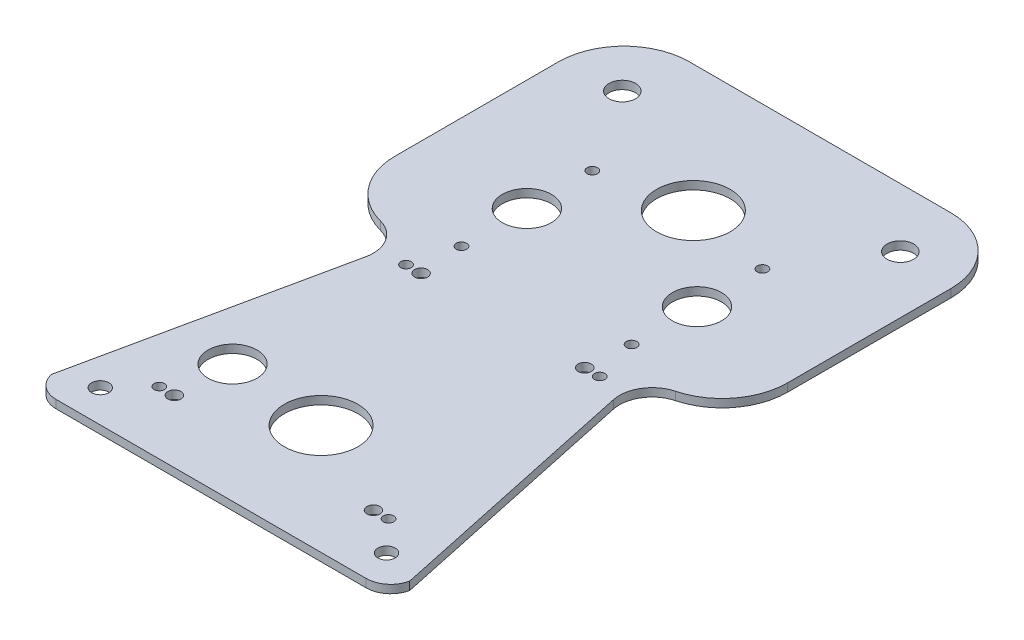
SolidWorks part; units mm, degrees
material "6061-T6 (SS)"
ref_plane "Front Plane" through (0, 0, 0) normal (0, 0, 1) x (1, 0, 0)
ref_plane "Top Plane" through (0, 0, 0) normal (0, 1, 0) x (1, 0, 0)
ref_plane "Right Plane" through (0, 0, 0) normal (1, 0, 0) x (0, 0, -1)
ref_plane "Plane1" through (0, 3.175, 0) normal (0, 1, 0) x (1, 0, 0)
sketch "Sketch1" plane through (0, 3.175, 0) normal (0, 1, 0) x (1, 0, 0)
  line L0 (457.2, 73.787) -> (457.2, -3.937)
  line L1 (457.2, -3.937) -> (812.8, -3.937)
  line L2 (812.8, -3.937) -> (812.8, 73.787)
  line L3 (812.8, 73.787) -> (457.2, 73.787)
  dimension "D1" = 355.6
extrude "Boss-Extrude1" add sketch "Sketch1" against normal blind 22.225
sketch "Sketch2" plane through (812.8, 0, 0) normal (1, 0, 0) x (0, 0, -1)
  line L0 (70.612, -19.05) -> (70.612, 0)
  line L1 (70.612, 0) -> (-3.937, 0)
  line L2 (-3.937, 0) -> (-3.937, -19.05)
  line L3 (-3.937, -19.05) -> (70.612, -19.05)
extrude "Cut-Extrude1" cut sketch "Sketch2" against normal through all
sketch "Sketch3" plane through (0, 3.175, 0) normal (0, 1, 0) x (-1, 0, 0)
  line L0 (-482.6, 3.937) -> (-482.6, 0)
  line L1 (-482.6, 0) -> (-457.2, 0)
  line L2 (-457.2, 0) -> (-457.2, 3.937)
  line L3 (-457.2, 3.937) -> (-482.6, 3.937)
extrude "Cut-Extrude2" cut sketch "Sketch3" against normal through all
sketch "Sketch4" plane through (0, 3.175, 0) normal (0, 1, 0) x (-1, 0, 0)
  line L0 (-812.8, 3.937) -> (-482.6, 3.937)
  line L1 (-482.6, 3.937) -> (-482.6, 0.762)
  line L2 (-482.6, 0.762) -> (-812.8, 0.762)
  line L3 (-812.8, 0.762) -> (-812.8, 3.937)
extrude "Boss-Extrude2" add sketch "Sketch4" along normal blind 15.875
sketch "Sketch5" plane through (457.2, 0, 0) normal (-1, 0, 0) x (0, 0, 1)
  line L0 (0, 3.175) -> (0, 0)
  line L1 (0, 0) -> (-69.85, 0)
  line L2 (-69.85, 0) -> (-69.85, 3.175)
  line L3 (-69.85, 3.175) -> (0, 3.175)
extrude "Boss-Extrude3" add sketch "Sketch5" along normal blind 457.2
sketch "Sketch6" plane through (0, 0, 0) normal (0, 0, 1) x (1, 0, 0)
  line L0 (330.2, 3.175) -> (330.2, 0)
  line L1 (330.2, 0) -> (0, 0)
  line L2 (0, 0) -> (0, 3.175)
  line L3 (0, 3.175) -> (330.2, 3.175)
extrude "Boss-Extrude4" add sketch "Sketch6" along normal blind 3.937
sketch "Sketch7" plane through (0, 3.175, 0) normal (0, 1, 0) x (-1, 0, 0)
  line L0 (-330.2, 3.937) -> (0, 3.937)
  line L1 (0, 3.937) -> (0, 0.762)
  line L2 (0, 0.762) -> (-330.2, 0.762)
  line L3 (-330.2, 0.762) -> (-330.2, 3.937)
extrude "Boss-Extrude5" add sketch "Sketch7" along normal blind 15.875
sketch "Sketch8" plane through (0, 0, -69.85) normal (0, 0, -1) x (-1, 0, 0)
  line L0 (-355.6, 0) -> (-355.6, 3.175)
  line L1 (-355.6, 3.175) -> (0, 3.175)
  line L2 (0, 3.175) -> (0, 0)
  line L3 (0, 0) -> (-355.6, 0)
extrude "Boss-Extrude6" add sketch "Sketch8" along normal blind 3.937
sketch "Sketch9" plane through (0, 0, 0) normal (0, -1, 0) x (1, 0, 0)
  line L0 (0, -70.612) -> (355.6, -70.612)
  line L1 (355.6, -70.612) -> (355.6, -73.787)
  line L2 (355.6, -73.787) -> (0, -73.787)
  line L3 (0, -73.787) -> (0, -70.612)
extrude "Boss-Extrude7" add sketch "Sketch9" along normal blind 19.05
sketch "Sketch10" plane through (0, 0, -69.85) normal (0, 0, -1) x (-1, 0, 0)
  line L0 (-444.5794, 3.175) -> (-368.2206, 3.175)
  line L1 (-368.2206, 3.175) -> (-368.2206, 0)
  line L2 (-368.2206, 0) -> (-444.5794, 0)
  line L3 (-444.5794, 0) -> (-444.5794, 3.175)
extrude "Boss-Extrude8" add sketch "Sketch10" along normal blind 27.432
sketch "Sketch11" plane through (0, 0, 0) normal (0, 0, 1) x (1, 0, 0)
  line L0 (344.3735, 3.175) -> (468.4265, 3.175)
  line L1 (468.4265, 3.175) -> (468.4265, 0)
  line L2 (468.4265, 0) -> (344.3735, 0)
  line L3 (344.3735, 0) -> (344.3735, 3.175)
extrude "Boss-Extrude9" add sketch "Sketch11" along normal blind 19.05
draft "Draft1" type of draft neutral plane draft angle 30 faces to draft 2 face at (344.3735, 1.5875, 9.525) face at (468.4265, 1.5875, 9.525) neutral plane through (0, 0, 19.05) neutral plane normal (0, 0, 1) parameters "D1"=30
draft "Draft2" type of draft neutral plane draft angle 19 faces to draft 2 face at (368.2206, 1.5875, -83.566) face at (444.5794, 1.5875, -83.566) neutral plane through (0, 0, -97.282) neutral plane normal (0, 0, -1) parameters "D1"=19
hole_wizard "M20 Clearance Hole1" positions "Sketch13" profile "Sketch12" hole size "M20" standard "ANSI Metric"
sketch "Sketch13" plane through (0, 0, 0) normal (0, -1, 0) x (-1, 0, 0)
  point P0 (-624.2546, 36.83)
sketch "Sketch12" plane through (624.2546, 0, -36.83) normal (1, 0, 0) x (0, 0, -1)
  line L0 (0, 0) -> (0, 19.05)
  line L1 (0, 19.05) -> (11.1125, 19.05)
  line L2 (11.1125, 19.05) -> (11.1125, 0)
  line L5 (11.1125, 0) -> (0, 0)
  line L11 (0, -6.35) -> (0, 107.95) construction
  dimension "Thru Hole Dia." = 22.225
  dimension "Thru Hole Depth" = 19.05
hole_wizard "Hole1" positions "Sketch15" profile "Sketch14" legacy
sketch "Sketch15" plane through (0, 3.175, 0) normal (0, 1, 0) x (1, 0, 0)
  point P0 (229.2616, 36.83)
  point P1 (229.2616, 62.23)
  point P2 (229.2616, 11.43)
sketch "Sketch14" plane through (229.2616, 3.175, -36.83) normal (1, 0, 0) x (0, 0, 1)
  line L0 (0, 0) -> (0, 22.225)
  line L1 (0, 22.225) -> (4.064, 22.225)
  line L2 (4.064, 22.225) -> (4.064, 0)
  line L3 (4.064, 0) -> (0, 0)
  line L4 (0, 110) -> (0, -10) construction
  dimension "Diameter" = 8.128
  dimension "Depth" = 22.225
hole_wizard "M25 Clearance Hole1" positions "Sketch17" profile "Sketch16" hole size "M25" standard "ANSI Metric"
sketch "Sketch17" plane through (0, 3.175, 0) normal (0, 1, 0) x (1, 0, 0)
  point P0 (147.8292, 36.83)
sketch "Sketch16" plane through (147.8292, 3.175, -36.83) normal (1, 0, 0) x (0, 0, 1)
  line L0 (0, 0) -> (0, 22.225)
  line L1 (0, 22.225) -> (14.2875, 22.225)
  line L2 (14.2875, 22.225) -> (14.2875, 0)
  line L5 (14.2875, 0) -> (0, 0)
  line L11 (0, -6.35) -> (0, 107.95) construction
  dimension "Thru Hole Dia." = 28.575
  dimension "Thru Hole Depth" = 22.225
hole_wizard "M3 Clearance Hole1" positions "Sketch19" profile "Sketch18" hole size "M3" standard "ANSI Metric"
sketch "Sketch19" plane through (0, 3.175, 0) normal (0, 1, 0) x (1, 0, 0)
  point P0 (120.6004, 65.405)
  point P1 (120.6004, 8.255)
  point P2 (237.4404, 8.255)
  point P3 (237.4404, 65.405)
sketch "Sketch18" plane through (120.6004, 3.175, -65.405) normal (1, 0, 0) x (0, 0, 1)
  line L0 (0, 0) -> (0, 22.225)
  line L1 (0, 22.225) -> (1.7859, 22.225)
  line L2 (1.7859, 22.225) -> (1.7859, 0)
  line L5 (1.7859, 0) -> (0, 0)
  line L11 (0, -6.35) -> (0, 107.95) construction
  dimension "Thru Hole Dia." = 3.5719
  dimension "Thru Hole Depth" = 22.225
hole_wizard "M2 Clearance Hole1" positions "Sketch21" profile "Sketch20" hole size "M2" standard "ANSI Metric"
sketch "Sketch21" plane through (0, 3.175, 0) normal (0, 1, 0) x (1, 0, 0)
  point P0 (101.6, 3.175)
  point P1 (101.6, 66.675)
  point P2 (50.8, 66.675)
  point P3 (50.8, 3.175)
  point P4 (762, 66.675)
  point P5 (762, 3.175)
  point P6 (711.2, 3.175)
  point P7 (711.2, 66.675)
sketch "Sketch20" plane through (101.6, 3.175, -3.175) normal (1, 0, 0) x (0, 0, 1)
  line L0 (0, 0) -> (0, 22.225)
  line L1 (0, 22.225) -> (1.27, 22.225)
  line L2 (1.27, 22.225) -> (1.27, 0)
  line L5 (1.27, 0) -> (0, 0)
  line L11 (0, -6.35) -> (0, 107.95) construction
  dimension "Thru Hole Dia." = 2.54
  dimension "Thru Hole Depth" = 22.225
hole_wizard "M3.5 Clearance Hole1" positions "Sketch23" profile "Sketch22" hole size "M3.5" standard "ANSI Metric"
sketch "Sketch23" plane through (0, 3.175, 0) normal (0, 1, 0) x (1, 0, 0)
  point P0 (443.992, 87.8535)
  point P1 (368.808, 87.8535)
  point P2 (361.9119, -1.0389)
  point P3 (450.8881, -1.0389)
sketch "Sketch22" plane through (443.992, 3.175, -87.8535) normal (1, 0, 0) x (0, 0, 1)
  line L0 (0, 0) -> (0, 22.225)
  line L1 (0, 22.225) -> (2.032, 22.225)
  line L2 (2.032, 22.225) -> (2.032, 0)
  line L5 (2.032, 0) -> (0, 0)
  line L11 (0, -6.35) -> (0, 107.95) construction
  dimension "Thru Hole Dia." = 4.064
  dimension "Thru Hole Depth" = 22.225
hole_wizard "Hole2" positions "Sketch25" profile "Sketch24" legacy
sketch "Sketch25" plane through (0, 3.175, 0) normal (0, 1, 0) x (1, 0, 0)
  point P0 (438.15, 87.8535)
  point P1 (374.65, 87.8535)
  point P2 (445.0461, -1.0389)
  point P3 (367.7539, -1.0389)
  point P4 (115.5204, 65.405)
  point P5 (115.5204, 8.255)
  point P6 (242.5204, 8.255)
  point P7 (242.5204, 65.405)
sketch "Sketch24" plane through (438.15, 3.175, -87.8535) normal (1, 0, 0) x (0, 0, 1)
  line L0 (0, 0) -> (0, 22.225)
  line L1 (0, 22.225) -> (2.54, 22.225)
  line L2 (2.54, 22.225) -> (2.54, 0)
  line L3 (2.54, 0) -> (0, 0)
  line L4 (0, 110) -> (0, -10) construction
  dimension "Diameter" = 5.08
  dimension "Depth" = 22.225
hole_wizard "M20 Clearance Hole2" [suppressed] positions "Sketch27" profile "Sketch26" hole size "M20" standard "ANSI Metric"
sketch "Sketch27" plane through (0, 3.175, 0) normal (0, 1, 0) x (1, 0, 0)
  point P0 (406.4, 57.9628)
  point P1 (188.5454, 36.83)
sketch "Sketch26" plane through (406.4, 3.175, -57.9628) normal (1, 0, 0) x (0, 0, 1)
  line L0 (0, 0) -> (0, 22.225)
  line L1 (0, 22.225) -> (11.1125, 22.225)
  line L2 (11.1125, 22.225) -> (11.1125, 0)
  line L5 (11.1125, 0) -> (0, 0)
  line L11 (0, -6.35) -> (0, 107.95) construction
  dimension "Thru Hole Dia." = 22.225
  dimension "Thru Hole Depth" = 22.225
hole_wizard "M25 Clearance Hole2" positions "Sketch31" profile "Sketch30" hole size "M25" standard "ANSI Metric"
sketch "Sketch31" plane through (0, 0, 0) normal (0, -1, 0) x (-1, 0, 0)
  point P0 (-406.4, 17.272)
  point P1 (-664.9708, 36.83)
sketch "Sketch30" plane through (406.4, 0, -17.272) normal (1, 0, 0) x (0, 0, -1)
  line L0 (0, 0) -> (0, 19.05)
  line L1 (0, 19.05) -> (14.2875, 19.05)
  line L2 (14.2875, 19.05) -> (14.2875, 0)
  line L5 (14.2875, 0) -> (0, 0)
  line L11 (0, -6.35) -> (0, 107.95) construction
  dimension "Thru Hole Dia." = 28.575
  dimension "Thru Hole Depth" = 19.05
hole_wizard "Hole3" positions "Sketch33" profile "Sketch32" legacy
sketch "Sketch33" plane through (0, 0, 0) normal (0, -1, 0) x (-1, 0, 0)
  point P0 (-570.2796, 8.255)
  point P1 (-570.2796, 65.405)
  point P2 (-697.2796, 65.405)
  point P3 (-697.2796, 8.255)
sketch "Sketch32" plane through (570.2796, 0, -8.255) normal (1, 0, 0) x (0, 0, -1)
  line L0 (0, 0) -> (0, 19.05)
  line L1 (0, 19.05) -> (2.5527, 19.05)
  line L2 (2.5527, 19.05) -> (2.5527, 0)
  line L3 (2.5527, 0) -> (0, 0)
  line L4 (0, 110) -> (0, -10) construction
  dimension "Diameter" = 5.1054
  dimension "Depth" = 19.05
hole_wizard "Hole4" positions "Sketch35" profile "Sketch34" legacy
sketch "Sketch35" plane through (0, 0, 0) normal (0, -1, 0) x (-1, 0, 0)
  point P0 (-583.5384, 11.43)
  point P1 (-583.5384, 36.83)
  point P2 (-583.5384, 62.23)
sketch "Sketch34" plane through (583.5384, 0, -11.43) normal (1, 0, 0) x (0, 0, -1)
  line L0 (0, 0) -> (0, 19.05)
  line L1 (0, 19.05) -> (4.064, 19.05)
  line L2 (4.064, 19.05) -> (4.064, 0)
  line L3 (4.064, 0) -> (0, 0)
  line L4 (0, 110) -> (0, -10) construction
  dimension "Diameter" = 8.128
  dimension "Depth" = 19.05
hole_wizard "M3 Clearance Hole2" positions "Sketch37" profile "Sketch36" hole size "M3" standard "ANSI Metric"
sketch "Sketch37" plane through (0, 0, 0) normal (0, -1, 0) x (-1, 0, 0)
  point P0 (-692.1996, 8.255)
  point P1 (-692.1996, 65.405)
  point P2 (-575.3596, 65.405)
  point P3 (-575.3596, 8.255)
sketch "Sketch36" plane through (692.1996, 0, -8.255) normal (1, 0, 0) x (0, 0, -1)
  line L0 (0, 0) -> (0, 19.05)
  line L1 (0, 19.05) -> (1.7859, 19.05)
  line L2 (1.7859, 19.05) -> (1.7859, 0)
  line L5 (1.7859, 0) -> (0, 0)
  line L11 (0, -6.35) -> (0, 107.95) construction
  dimension "Thru Hole Dia." = 3.5719
  dimension "Thru Hole Depth" = 19.05
hole_wizard "M6 Clearance Hole1" positions "Sketch39" profile "Sketch38" hole size "M6" standard "ANSI Metric"
sketch "Sketch39" plane through (0, 3.175, 0) normal (0, 1, 0) x (1, 0, 0)
  point P0 (612.775, 10.287)
  point P1 (498.475, 10.287)
  point P2 (314.325, 10.287)
  point P3 (200.025, 10.287)
  point P4 (628.3192, 61.976)
  point P5 (184.4808, 61.976)
  point P6 (690.88, 15.875)
  point P7 (739.902, 9.525)
  point P8 (121.92, 15.875)
  point P9 (72.898, 9.525)
  point P10 (298.8745, 17.5473)
  point P11 (513.9255, 17.5473)
  point P12 (165.1, 14.732)
  point P13 (266.7, 14.732)
  point P14 (546.1, 14.732)
  point P15 (647.7, 14.732)
  point P16 (330.2, 61.722)
  point P17 (279.4, 61.722)
  point P18 (139.7, 61.722)
  point P19 (25.4, 61.722)
  point P20 (482.6, 61.722)
  point P21 (533.4, 61.722)
  point P22 (673.1, 61.722)
  point P23 (787.4, 61.722)
  point P24 (6.35, 39.497)
  point P25 (806.45, 39.497)
  point P26 (350.8375, -12.8905)
  point P27 (461.9625, -12.8905)
sketch "Sketch38" plane through (612.775, 3.175, -10.287) normal (1, 0, 0) x (0, 0, 1)
  line L0 (0, 0) -> (0, 22.225)
  line L1 (0, 22.225) -> (3.3528, 22.225)
  line L2 (3.3528, 22.225) -> (3.3528, 0)
  line L5 (3.3528, 0) -> (0, 0)
  line L11 (0, -6.35) -> (0, 107.95) construction
  dimension "Thru Hole Dia." = 6.7056
  dimension "Thru Hole Depth" = 22.225
hole_wizard "M6 Clearance Hole2" positions "Sketch41" profile "Sketch40" hole size "M6" standard "ANSI Metric"
sketch "Sketch41" plane through (0, 0, 3.937) normal (0, 0, 1) x (1, 0, 0)
  point P0 (495.3, 12.7)
  point P1 (520.7, 12.7)
  point P2 (546.1, 12.7)
  point P3 (571.5, 12.7)
  point P4 (596.9, 12.7)
  point P5 (622.3, 12.7)
  point P6 (647.7, 12.7)
  point P7 (673.1, 12.7)
  point P8 (698.5, 12.7)
  point P9 (723.9, 12.7)
  point P10 (749.3, 12.7)
  point P11 (774.7, 12.7)
  point P12 (800.1, 12.7)
  point P13 (317.5, 12.7)
  point P14 (292.1, 12.7)
  point P15 (266.7, 12.7)
  point P16 (241.3, 12.7)
  point P17 (215.9, 12.7)
  point P18 (190.5, 12.7)
  point P19 (165.1, 12.7)
  point P20 (139.7, 12.7)
  point P21 (114.3, 12.7)
  point P22 (88.9, 12.7)
  point P23 (63.5, 12.7)
  point P24 (12.7, 12.7)
  point P25 (38.1, 12.7)
sketch "Sketch40" plane through (495.3, 12.7, 3.937) normal (1, 0, 0) x (0, -1, 0)
  line L0 (0, 0) -> (0, 101.219)
  line L1 (0, 101.219) -> (3.3528, 101.219)
  line L2 (3.3528, 101.219) -> (3.3528, 0)
  line L5 (3.3528, 0) -> (0, 0)
  line L11 (0, -6.35) -> (0, 107.95) construction
  dimension "Thru Hole Dia." = 6.7056
  dimension "Thru Hole Depth" = 101.219
hole_wizard "M5 Clearance Hole1" positions "Sketch43" profile "Sketch42" hole size "M5" standard "ANSI Metric"
sketch "Sketch43" plane through (0, 0, -73.787) normal (0, 0, -1) x (-1, 0, 0)
  point P0 (-469.9, -12.7)
  point P1 (-495.3, -12.7)
  point P2 (-520.7, -12.7)
  point P3 (-546.1, -12.7)
  point P4 (-571.5, -12.7)
  point P5 (-596.9, -12.7)
  point P6 (-622.3, -12.7)
  point P7 (-647.7, -12.7)
  point P8 (-673.1, -12.7)
  point P9 (-698.5, -12.7)
  point P10 (-723.9, -12.7)
  point P11 (-749.3, -12.7)
  point P12 (-774.7, -12.7)
  point P13 (-800.1, -12.7)
  point P14 (-342.9, -12.7)
  point P15 (-317.5, -12.7)
  point P16 (-292.1, -12.7)
  point P17 (-266.7, -12.7)
  point P18 (-241.3, -12.7)
  point P19 (-215.9, -12.7)
  point P20 (-190.5, -12.7)
  point P21 (-165.1, -12.7)
  point P22 (-139.7, -12.7)
  point P23 (-114.3, -12.7)
  point P24 (-88.9, -12.7)
  point P25 (-63.5, -12.7)
  point P26 (-38.1, -12.7)
  point P27 (-12.7, -12.7)
sketch "Sketch42" plane through (469.9, -12.7, -73.787) normal (1, 0, 0) x (0, 1, 0)
  line L0 (0, 0) -> (0, 92.837)
  line L1 (0, 92.837) -> (2.667, 92.837)
  line L2 (2.667, 92.837) -> (2.667, 0)
  line L5 (2.667, 0) -> (0, 0)
  line L11 (0, -6.35) -> (0, 107.95) construction
  dimension "Thru Hole Dia." = 5.334
  dimension "Thru Hole Depth" = 92.837
chamfer "Chamfer1" distance 3.175 angle 45 8 edges at (482.6, 19.05, 2.3495) (0, 19.05, 2.3495) (812.8, 19.05, 2.3495) (812.8, -19.05, -72.1995) (457.2, -19.05, -72.1995) (0, -19.05, -72.1995) (330.2, 19.05, 2.3495) (355.6, -19.05, -72.1995)
fillet "Fillet1" radius 0.762 4 edges at (177.8, 0, -70.612) (635, 0, -70.612) (165.1, 3.175, 0.762)
fillet "Fillet2" radius 3.175 8 edges at (368.2206, 1.5875, -97.282) (333.375, 1.5875, 0) (344.3735, 1.5875, 19.05) (444.5794, 1.5875, -97.282) (358.775, 1.5875, -69.85) (479.425, 1.5875, 0) (468.4265, 1.5875, 19.05) (454.025, 1.5875, -69.85)
fillet "Fillet3" radius 3.937 4 edges at (165.1, 0, 3.937) (647.7, 0, 3.937) (635, 3.175, -73.787) (177.8, 3.175, -73.787)
sketch "Sketch44" plane through (0, 3.175, 0) normal (0, 1, 0) x (1, 0, 0)
  line L0 (367.4833, 95.1407) -> (343.457, -17.4625)
  line L1 (343.457, -17.4625) -> (339.5643, -35.7062)
  line L2 (367.4833, 95.1407) -> (367.4833, 120.6092)
  line L3 (367.4833, 120.6092) -> (-19.7867, 120.6092)
  line L4 (-19.7867, 120.6092) -> (-19.7867, -35.7062)
  line L5 (-19.7867, -35.7062) -> (339.5643, -35.7062)
  line L6 (406.4, 97.282) -> (406.4, -19.05) construction
  line L7 (370.4853, 97.282) -> (442.3147, 97.282) construction
  line L8 (466.5934, -19.05) -> (346.2066, -19.05) construction
  line L9 (445.3167, 95.1407) -> (445.3167, 120.6092)
  line L10 (445.3167, 95.1407) -> (469.343, -17.4625)
  line L11 (469.343, -17.4625) -> (473.2357, -35.7062)
  line L12 (832.5867, -35.7062) -> (473.2357, -35.7062)
  line L13 (832.5867, 120.6092) -> (832.5867, -35.7062)
  line L14 (445.3167, 120.6092) -> (832.5867, 120.6092)
  dimension "D1" = 156.3154
  dimension "D2" = 387.27
  dimension "D3" = 90
  dimension "D4" = 102.045
  dimension "D5" = 18.2437
extrude "Cut-Extrude3" cut sketch "Sketch44" against normal through all both and the other way through all
sketch "Sketch45" plane through (0, 3.175, 0) normal (0, 1, 0) x (1, 0, 0)
  line L24 (343.457, -17.4625) -> (367.4833, 95.1407) construction
  line L25 (370.4853, 97.282) -> (442.3147, 97.282) construction
  line L26 (445.3167, 95.1407) -> (469.343, -17.4625) construction
  line L27 (466.5934, -19.05) -> (346.2066, -19.05) construction
  line L28 (346.2066, -25.4) -> (466.5934, -25.4)
  line L29 (475.915, -17.8329) -> (451.468, 96.7418)
  line L30 (442.3147, 103.632) -> (370.4853, 103.632)
  line L31 (361.332, 96.7418) -> (336.885, -17.8329)
  line L32 (346.2066, -25.4) -> (466.5934, -25.4)
  line L33 (475.915, -17.8329) -> (451.468, 96.7418)
  line L34 (442.3147, 103.632) -> (370.4853, 103.632)
  line L35 (361.332, 96.7418) -> (336.885, -17.8329)
  line L36 (343.457, -17.4625) -> (367.4833, 95.1407)
  line L37 (370.4853, 97.282) -> (442.3147, 97.282)
  line L38 (445.3167, 95.1407) -> (469.343, -17.4625)
  line L39 (466.5934, -19.05) -> (346.2066, -19.05)
  arc A21 (370.4853, 97.282) -> (367.4833, 95.1407) centre (370.4853, 94.107) ccw construction
  arc A22 (445.3167, 95.1407) -> (442.3147, 97.282) centre (442.3147, 94.107) ccw construction
  arc A23 (466.5934, -19.05) -> (469.343, -17.4625) centre (466.5934, -15.875) ccw construction
  arc A24 (343.457, -17.4625) -> (346.2066, -19.05) centre (346.2066, -15.875) ccw construction
  arc A25 (336.885, -17.8329) -> (346.2066, -25.4) centre (346.2066, -15.875) ccw
  arc A26 (466.5934, -25.4) -> (475.915, -17.8329) centre (466.5934, -15.875) ccw
  arc A27 (451.468, 96.7418) -> (442.3147, 103.632) centre (442.3147, 94.107) ccw
  arc A28 (370.4853, 103.632) -> (361.332, 96.7418) centre (370.4853, 94.107) ccw
  arc A29 (336.885, -17.8329) -> (346.2066, -25.4) centre (346.2066, -15.875) ccw
  arc A30 (466.5934, -25.4) -> (475.915, -17.8329) centre (466.5934, -15.875) ccw
  arc A31 (451.468, 96.7418) -> (442.3147, 103.632) centre (442.3147, 94.107) ccw
  arc A32 (370.4853, 103.632) -> (361.332, 96.7418) centre (370.4853, 94.107) ccw
  arc A33 (370.4853, 97.282) -> (367.4833, 95.1407) centre (370.4853, 94.107) ccw
  arc A34 (445.3167, 95.1407) -> (442.3147, 97.282) centre (442.3147, 94.107) ccw
  arc A35 (466.5934, -19.05) -> (469.343, -17.4625) centre (466.5934, -15.875) ccw
  arc A36 (343.457, -17.4625) -> (346.2066, -19.05) centre (346.2066, -15.875) ccw
  dimension "D1" = 6.35
extrude "Boss-Extrude10" add sketch "Sketch45" against normal up to surface (3.175 mm away) up to face at (350.8375, 0, 16.2433)
sketch "Sketch46" plane through (0, 3.175, 0) normal (0, 1, 0) x (1, 0, 0)
  line L0 (361.332, 96.7418) -> (330.2, 96.7418)
  line L1 (330.2, 96.7418) -> (330.2, 211.0418)
  line L2 (330.2, 211.0418) -> (482.6, 211.0418)
  line L3 (482.6, 211.0418) -> (482.6, 96.7418)
  line L4 (482.6, 96.7418) -> (451.468, 96.7418)
  line L5 (406.4, 211.0418) -> (406.4, 103.632) construction
  line L6 (442.3147, 103.632) -> (370.4853, 103.632) construction
  line L7 (442.3147, 103.632) -> (370.4853, 103.632)
  arc A0 (370.4853, 103.632) -> (361.332, 96.7418) centre (370.4853, 94.107) ccw construction
  arc A1 (451.468, 96.7418) -> (442.3147, 103.632) centre (442.3147, 94.107) ccw construction
  arc A2 (370.4853, 103.632) -> (361.332, 96.7418) centre (370.4853, 94.107) ccw
  arc A3 (451.468, 96.7418) -> (442.3147, 103.632) centre (442.3147, 94.107) ccw
  dimension "D1" = 152.4
  dimension "D2" = 114.3
extrude "Boss-Extrude11" add sketch "Sketch46" against normal up to surface (3.175 mm away) contours L1 L2 L3 L4 A3 L7 A2 L0 up to face at (350.8375, 0, 16.2433)
fillet "Fillet4" radius 25.4 4 edges at (330.2, 1.5875, -96.7418) (330.2, 1.5875, -211.0418) (482.6, 1.5875, -211.0418) (482.6, 1.5875, -96.7418)
fillet "Fillet5" radius 12.7 2 edges at (361.332, 1.5875, -96.7418) (451.468, 1.5875, -96.7418)
sketch "Sketch47" plane through (0, 3.175, 0) normal (0, 1, 0) x (1, 0, 0)
  line L0 (356.7202, 91.952) -> (456.0798, 91.952) construction
  circle A0 centre (406.4, 161.802) radius 14.2875
  circle A1 centre (368.5585, 20.7395) radius 8.5
  circle A2 centre (406.4, 17.272) radius 30 construction
  circle A3 centre (368.5585, 20.7395) radius 8 construction
  circle A4 centre (439.42, 130.1793) radius 9.525
  circle A5 centre (373.38, 130.1793) radius 9.525
  circle A6 centre (373.38, 130.1793) radius 31.75 construction
  circle A7 centre (439.42, 130.1793) radius 31.75 construction
  circle A8 centre (373.38, 130.1793) radius 22.86 construction
  circle A9 centre (439.42, 130.1793) radius 22.86 construction
  circle A10 centre (406.4, 161.802) radius 22.86 construction
  circle A11 centre (368.5585, 20.7395) radius 41.91 construction
  circle A12 centre (406.4, 161.802) radius 41.91 construction
  arc A13 (463.664, 97.5781) -> (454.4757, 82.6461) centre (466.8961, 85.2962) ccw construction
  arc A14 (358.3243, 82.6461) -> (349.136, 97.5781) centre (345.9039, 85.2962) ccw construction
  circle A15 centre (373.38, 155.5793) radius 2.032
  circle A16 centre (373.38, 104.7793) radius 2.032
  circle A17 centre (439.42, 155.5793) radius 2.032
  circle A18 centre (439.42, 104.7793) radius 2.032
  dimension "D1" = 28.575
  dimension "D2" = 17
  dimension "D4" = 60
  dimension "D5" = 16
  dimension "D9" = 63.5
  dimension "D10" = 19.05
  dimension "D8" = 83.82
  dimension "D13" = 4.064
  dimension "D3" = 146.05
  dimension "D6" = 45.72
  dimension "D7" = 45.72
  dimension "D11" = 66.04
  dimension "D12" = 69.85
  dimension "D14" = 25.4
  dimension "D15" = 50.8
  dimension "D16" = 25.4
  dimension "D17" = 50.8
extrude "Cut-Extrude4" cut sketch "Sketch47" against normal through all
sketch "Sketch48" [suppressed] plane through (0, 0, 0) normal (0, -1, 0) x (-1, 0, 0)
  line L0 (-726.4609, 20.828) -> (-701.4504, 20.828) construction
  line L1 (-701.4504, 20.828) -> (-678.0541, 20.828) construction
  line L2 (-809.625, 73.787) -> (-460.375, 73.787) construction
  line L3 (-628.9477, 19.05) -> (-601.4385, 19.05) construction
  line L4 (-601.4385, 19.05) -> (-568.9249, 19.05) construction
  line L5 (-406.4, 97.282) -> (-406.4, -19.05) construction
  line L6 (-442.3147, 97.282) -> (-370.4853, 97.282) construction
  line L7 (-346.2066, -19.05) -> (-466.5934, -19.05) construction
  circle A5 centre (-601.4385, 19.05) radius 4.826
  circle A6 centre (-628.9477, 19.05) radius 4.826
  circle A7 centre (-701.4504, 20.828) radius 4.826
  circle A8 centre (-726.4609, 20.828) radius 4.826
  circle A9 centre (-568.9249, 19.05) radius 4.826
  circle A10 centre (-406.4, 17.272) radius 15.5575 construction
  circle A11 centre (-406.4, 17.272) radius 14.2875 construction
  circle A12 centre (-678.0541, 20.828) radius 4.826
  circle A13 centre (-243.8751, 19.05) radius 4.826
  circle A14 centre (-211.3615, 19.05) radius 4.826
  circle A15 centre (-183.8523, 19.05) radius 4.826
  circle A16 centre (-134.7459, 20.828) radius 4.826
  circle A17 centre (-111.3496, 20.828) radius 4.826
  circle A18 centre (-86.3391, 20.828) radius 4.826
  dimension "D1" = 1.778
  dimension "D2" = 162.5249
  dimension "D3" = 9.652
  dimension "D6" = 295.0504
  dimension "D7" = 52.959
  dimension "D4" = 25.0105
  dimension "D5" = 23.3962
  dimension "D8" = 27.5092
  dimension "D9" = 32.5136
extrude "Cut-Extrude5" [suppressed] cut sketch "Sketch48" against normal through all
sketch "Sketch49" plane through (0, 3.175, 0) normal (0, 1, 0) x (1, 0, 0)
  line L0 (373.38, 130.1793) -> (406.4, 161.802) construction
  line L1 (406.4, 161.802) -> (439.42, 130.1793) construction
  line L2 (373.38, 130.1793) -> (439.42, 130.1793) construction
  line L3 (406.4, 161.802) -> (406.4, 211.0418) construction
  line L4 (355.6, 211.0418) -> (457.2, 211.0418) construction
  line L5 (356.7202, 91.952) -> (456.0798, 91.952) construction
  circle A0 centre (406.4, 161.802) radius 14.2875
  circle A1 centre (373.38, 130.1793) radius 9.525
  circle A2 centre (439.42, 130.1793) radius 9.525
  circle A3 centre (368.5585, 20.7395) radius 9.5
  circle A4 centre (406.4, 17.272) radius 30 construction
  circle A5 centre (368.5585, 20.7395) radius 8 construction
  arc A6 (358.3243, 82.6461) -> (349.136, 97.5781) centre (345.9039, 85.2962) ccw construction
  arc A7 (463.664, 97.5781) -> (454.4757, 82.6461) centre (466.8961, 85.2962) ccw construction
  circle A8 centre (368.5585, 20.7395) radius 44.196 construction
  circle A9 centre (373.38, 130.1793) radius 22.86 construction
  circle A10 centre (439.42, 130.1793) radius 22.86 construction
  circle A11 centre (406.4, 161.802) radius 22.86 construction
  circle A12 centre (406.4, 161.802) radius 44.196 construction
  circle A13 centre (373.38, 130.1793) radius 31.75 construction
  circle A14 centre (439.42, 130.1793) radius 31.75 construction
  dimension "D1" = 19.05
  dimension "D2" = 28.575
  dimension "D4" = 19
  dimension "D5" = 60
  dimension "D6" = 16
  dimension "D10" = 88.392
  dimension "D11" = 63.5
  dimension "D3" = 45.72
  dimension "D7" = 146.05
  dimension "D8" = 66.04
  dimension "D9" = 69.85
sketch "Sketch50" [suppressed] plane through (0, 3.175, 0) normal (0, 1, 0) x (1, 0, 0)
  line L0 (373.38, 155.5793) -> (373.38, 104.7793) construction
  line L1 (406.4, -25.4) -> (406.4, 211.0418) construction
  line L2 (355.6, 211.0418) -> (457.2, 211.0418) construction
  line L3 (346.2066, -25.4) -> (466.5934, -25.4) construction
  line L4 (439.42, 155.5793) -> (439.42, 104.7793) construction
  circle A0 centre (373.38, 155.5793) radius 2.032
  circle A1 centre (373.38, 104.7793) radius 2.032
  circle A2 centre (439.42, 155.5793) radius 2.032
  circle A3 centre (439.42, 104.7793) radius 2.032
  circle A4 centre (439.42, 130.1793) radius 9.525 construction
  point P15 (439.42, 130.1793)
  dimension "D1" = 50.8
  dimension "D2" = 4.064
extrude "Cut-Extrude7" [suppressed] cut sketch "Sketch50" against normal through all
sketch "Sketch52" plane through (0, 3.175, 0) normal (0, 1, 0) x (1, 0, 0)
  line L0 (349.795, 17.272) -> (432.345, 17.272) construction
  line L1 (349.795, 42.672) -> (432.345, 42.672)
  line L2 (349.795, 42.672) -> (349.795, -8.128)
  line L3 (349.795, -8.128) -> (432.345, -8.128)
  line L4 (432.345, 42.672) -> (432.345, -8.128)
  line L5 (358.3243, 82.6461) -> (336.885, -17.8329) construction
  point P8 (406.4, 17.272)
  dimension "D1" = 50.8
  dimension "D2" = 82.55
extrude "Cut-Extrude9" [suppressed] cut sketch "Sketch52" against normal through all flip side to cut
sketch "Sketch53" [suppressed] plane through (0, 3.175, 0) normal (0, 1, 0) x (1, 0, 0)
  line L0 (349.795, 42.672) -> (349.795, -8.128) construction
  line L2 (432.345, 42.672) -> (349.795, 42.672) construction
  line L3 (432.345, -8.128) -> (432.345, 42.672) construction
  line L4 (349.795, -8.128) -> (432.345, -8.128) construction
  circle A0 centre (425.995, 36.322) radius 2.7781
  circle A1 centre (425.995, -1.778) radius 2.7781
  circle A2 centre (356.145, 36.322) radius 2.7781
  dimension "D1" = 5.5562
  dimension "D2" = 6.35
  dimension "D3" = 6.35
  dimension "D4" = 6.35
  dimension "D5" = 6.35
  dimension "D6" = 6.35
  dimension "D7" = 6.35
extrude "Cut-Extrude10" [suppressed] cut sketch "Sketch53" against normal through all
sketch "Sketch54" plane through (0, 3.175, 0) normal (0, 1, 0) x (1, 0, 0)
  line L4 (432.345, 42.672) -> (349.795, 42.672)
  line L5 (432.345, -8.128) -> (432.345, 42.672)
  line L6 (349.795, -8.128) -> (432.345, -8.128)
  line L7 (349.795, 42.672) -> (349.795, -8.128)
  line L8 (432.345, 42.672) -> (349.795, 42.672) construction
  line L9 (432.345, -8.128) -> (432.345, 42.672) construction
  line L10 (349.795, -8.128) -> (432.345, -8.128) construction
  line L11 (349.795, 42.672) -> (349.795, -8.128) construction
  circle A0 centre (356.145, 36.322) radius 2.7781
  circle A1 centre (425.995, 36.322) radius 2.7781
  circle A2 centre (425.995, -1.778) radius 2.7781
  dimension "D2" = 5.5562
  dimension "D3" = 6.35
  dimension "D8" = 6.35
  dimension "D4" = 6.35
  dimension "D5" = 6.35
  dimension "D6" = 6.35
  dimension "D7" = 6.35
  dimension "D1" = 0
extrude "Cut-Extrude11" [suppressed] cut sketch "Sketch54" against normal through all contours A0
sketch "Sketch55" [suppressed] plane through (0, 3.175, 0) normal (0, 1, 0) x (1, 0, 0)
  line L0 (432.345, 42.672) -> (349.795, 42.672) construction
  line L1 (349.795, 42.672) -> (349.795, -8.128) construction
  line L2 (349.795, -8.128) -> (432.345, -8.128) construction
  line L3 (432.345, -8.128) -> (432.345, 42.672) construction
  line L4 (432.345, 42.672) -> (349.795, 42.672)
  line L5 (349.795, 42.672) -> (349.795, -8.128)
  line L6 (349.795, -8.128) -> (432.345, -8.128)
  line L7 (432.345, -8.128) -> (432.345, 42.672)
  circle A0 centre (356.145, 36.322) radius 2.7781 construction
  circle A1 centre (425.995, 36.322) radius 2.7781 construction
  circle A2 centre (425.995, -1.778) radius 2.7781 construction
  circle A3 centre (367.7539, -1.0389) radius 2.54 construction
  circle A4 centre (361.9119, -1.0389) radius 2.032 construction
  circle A5 centre (406.4, 17.272) radius 14.2875 construction
  circle A6 centre (356.145, 36.322) radius 2.7781
  circle A7 centre (425.995, 36.322) radius 2.7781
  circle A8 centre (425.995, -1.778) radius 2.7781
  circle A9 centre (367.7539, -1.0389) radius 2.54
  circle A10 centre (361.9119, -1.0389) radius 2.032
  circle A11 centre (406.4, 17.272) radius 14.2875
  circle A18 centre (368.5585, 20.7395) radius 8.5
  circle A19 centre (368.5585, 20.7395) radius 8.5
  dimension "D3" = 0
extrude "Cut-Extrude12" cut sketch "Sketch49" against normal blind 12.7 contours A3
extrude "Boss-Extrude12" [suppressed] add sketch "Sketch55" against normal blind 19.05
sketch "Sketch57" [suppressed] plane through (0, -15.875, 0) normal (0, -1, 0) x (1, 0, 0)
  circle A0 centre (368.5585, -20.7395) radius 8.5 construction
  circle A1 centre (368.5585, -20.7395) radius 8.5
extrude "Cut-Extrude13" [suppressed] cut sketch "Sketch57" against normal through all
sketch "Sketch58" plane through (0, 3.175, 0) normal (0, 1, 0) x (1, 0, 0)
  line L0 (406.4, 211.0418) -> (406.4, 189.645) construction
  line L1 (355.6, 211.0418) -> (457.2, 211.0418) construction
  circle A0 centre (352.425, 188.1818) radius 5.1594
  circle A1 centre (460.375, 188.1818) radius 5.1594
  dimension "D1" = 10.3187
  dimension "D2" = 107.95
  dimension "D3" = 53.975
  dimension "D4" = 22.86
extrude "Cut-Extrude14" cut sketch "Sketch58" against normal through all
sketch "Sketch59" plane through (0, 3.175, 0) normal (0, 1, 0) x (1, 0, 0)
  line L0 (469.0017, 124.3162) -> (397.128, -2.8246) construction
  line L1 (319.7379, 40.9246) -> (391.6116, 168.0654) construction
  line L2 (335.5511, 216.0228) -> (408.7166, 261.9016) construction
  line L4 (358.4329, 19.05) -> (430.3066, 146.1908) construction
  line L5 (269.6372, 76.2) -> (683.372, 76.2) construction
  line L6 (346.2066, -25.4) -> (466.5934, -25.4) construction
  line L7 (358.4329, 19.05) -> (406.4, 17.272) construction
  circle A0 centre (430.3066, 146.1908) radius 44.45 construction
  circle A1 centre (358.4329, 19.05) radius 44.45 construction
  circle A2 centre (357.1411, 181.592) radius 31.75
  circle A3 centre (430.3066, 227.4708) radius 31.75
  circle A4 centre (358.4329, 19.05) radius 9.5
  circle A5 centre (430.3066, 146.1908) radius 40.64
  circle A6 centre (357.1411, 181.592) radius 40.64
  circle A7 centre (430.3066, 227.4708) radius 40.64
  circle A8 centre (406.4, 17.272) radius 50 construction
  dimension "D1" = 88.9
  dimension "D2" = 63.5
  dimension "D3" = 81.28
  dimension "D4" = 100
  dimension "D7" = 19
  dimension "D5" = 101.6
  dimension "D6" = 48
  dimension "D8" = 146.05
  dimension "D9" = 86.36
sketch "Sketch60" plane through (0, 3.175, 0) normal (0, 1, 0) x (1, 0, 0)
  circle A0 centre (430.3066, 146.1908) radius 146.05 construction
  circle A1 centre (348.9075, 24.9275) radius 8 construction
  circle A2 centre (406.4, 17.272) radius 50 construction
  circle A3 centre (348.9075, 24.9275) radius 9.5
  circle A4 centre (368.5585, 20.7395) radius 9.5 construction
  circle A5 centre (406.4, 17.272) radius 40 construction
  circle A6 centre (451.8153, 1.7332) radius 8 construction
  circle A7 centre (451.8153, 1.7332) radius 9.5
  dimension "D1" = 16
  dimension "D2" = 80
  dimension "D3" = 16
equation "\"robotLength\" = 32in"
equation "\"robotWidth\" = 27in"
equation "\"cvtDisplacement\" = 5.75in"
equation "\"dropCenterdistance\" = .125in"
equation "\"centerWheel_outerWheel\" = 10in"
equation "\"railDisplacement\" = 5in"
equation "\"bearingOD\" = 1.125in"
equation "\"centerShaftheight\" = 1.5in"
equation "\"CIMplateHeight\" = 4.5in"
equation "\"CIMplateWidth\" = 6in"
equation "\"CIMplateDepth\" = .25in"
equation "\"AndymarkRailinnerRailcenterWidth\" = 4in"
equation "\"D1@Sketch1\"=\"robotLength\"/2 - \"AndymarkRailinnerRailcenterWidth\"/2"
equation "\"D1@Sketch46\"=\"CIMplateWidth\""
equation "\"D2@Sketch46\"=\"CIMplateHeight\""
equation "\"D3@Sketch47\"=\"cvtDisplacement\""
equation "\"Ms_to_Ds\" = 1.8in"
equation "\"D6@Sketch47\"=\"Ms_to_Ds\""
equation "\"D7@Sketch47\"=\"Ms_to_Ds\""
equation "\"D3@Sketch49\"=\"Ms_to_Ds\""
equation "\"D8@Sketch59\"=\"cvtDisplacement\""
